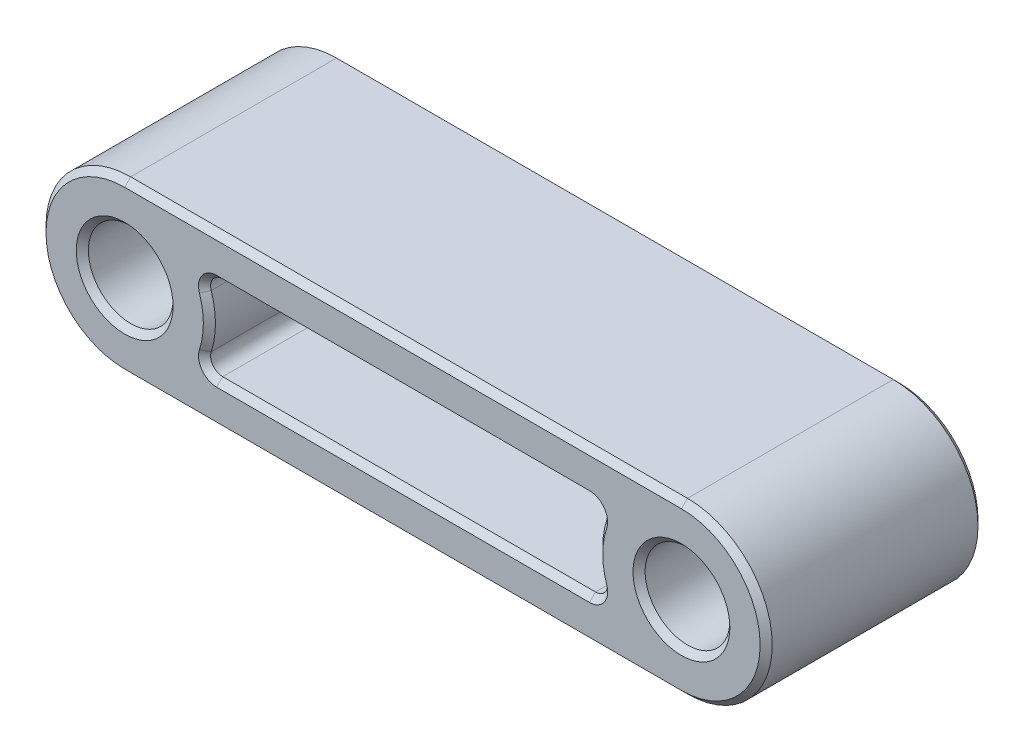
SolidWorks part; units mm, degrees
ref_plane "Front Plane" through (0, 0, 0) normal (0, 0, 1) x (1, 0, 0)
ref_plane "Top Plane" through (0, 0, 0) normal (0, 1, 0) x (1, 0, 0)
ref_plane "Right Plane" through (0, 0, 0) normal (1, 0, 0) x (0, 0, -1)
sketch "Sketch1" plane through (0, 0, 0) normal (0, 0, 1) x (1, 0, 0)
  line L0 (-11.5, 0) -> (11.5, 0) construction
  line L1 (-11.5, 3.5) -> (11.5, 3.5)
  line L2 (-11.5, -3.5) -> (11.5, -3.5)
  line L3 (-8.4689, 1.75) -> (8.4689, 1.75)
  line L4 (-8.4689, -1.75) -> (8.4689, -1.75)
  arc A0 (-11.5, 3.5) -> (-11.5, -3.5) centre (-11.5, 0) ccw
  arc A1 (11.5, -3.5) -> (11.5, 3.5) centre (11.5, 0) ccw
  circle A2 centre (-11.5, 0) radius 1.75
  circle A3 centre (11.5, 0) radius 1.75
  arc A4 (-8.4689, 1.75) -> (-8.4689, -1.75) centre (-11.5, 0) cw
  arc A5 (8.4689, 1.75) -> (8.4689, -1.75) centre (11.5, 0) ccw
  point P3 (0, 0)
  point P16 (0, 0)
  dimension "D2" = 3.5
  dimension "D3" = 3.5
  dimension "D4" = 3.5
  dimension "D1" = 23
extrude "Boss-Extrude1" add sketch "Sketch1" along normal blind 9
fillet "Fillet1" radius 0.5 4 edges at (8.4689, -1.75, 4.5) (8.4689, 1.75, 4.5) (-8.4689, 1.75, 4.5) (-8.4689, -1.75, 4.5)
chamfer "Chamfer2" distance 0.25 angle 45 28 edges at (8.1054, 1.5432, 0) (8, 0, 0) (8.1054, -1.5432, 0) (0, -1.75, 0) (-8.1054, -1.5432, 0) (-8, 0, 0) (-8.1054, 1.5432, 0) (0, 1.75, 0) (0, -3.5, 0) (15, 0, 0) (0, 3.5, 0) (-15, 0, 0) (13.25, 0, 0) (-9.75, 0, 0) (8.1054, -1.5432, 9) (8, 0, 9) (8.1054, 1.5432, 9) (0, 1.75, 9) (-8.1054, 1.5432, 9) (-8, 0, 9) (-8.1054, -1.5432, 9) (0, -1.75, 9) (-9.75, 0, 9) (0, 3.5, 9) (15, 0, 9) (0, -3.5, 9) (-15, 0, 9) (13.25, 0, 9)
